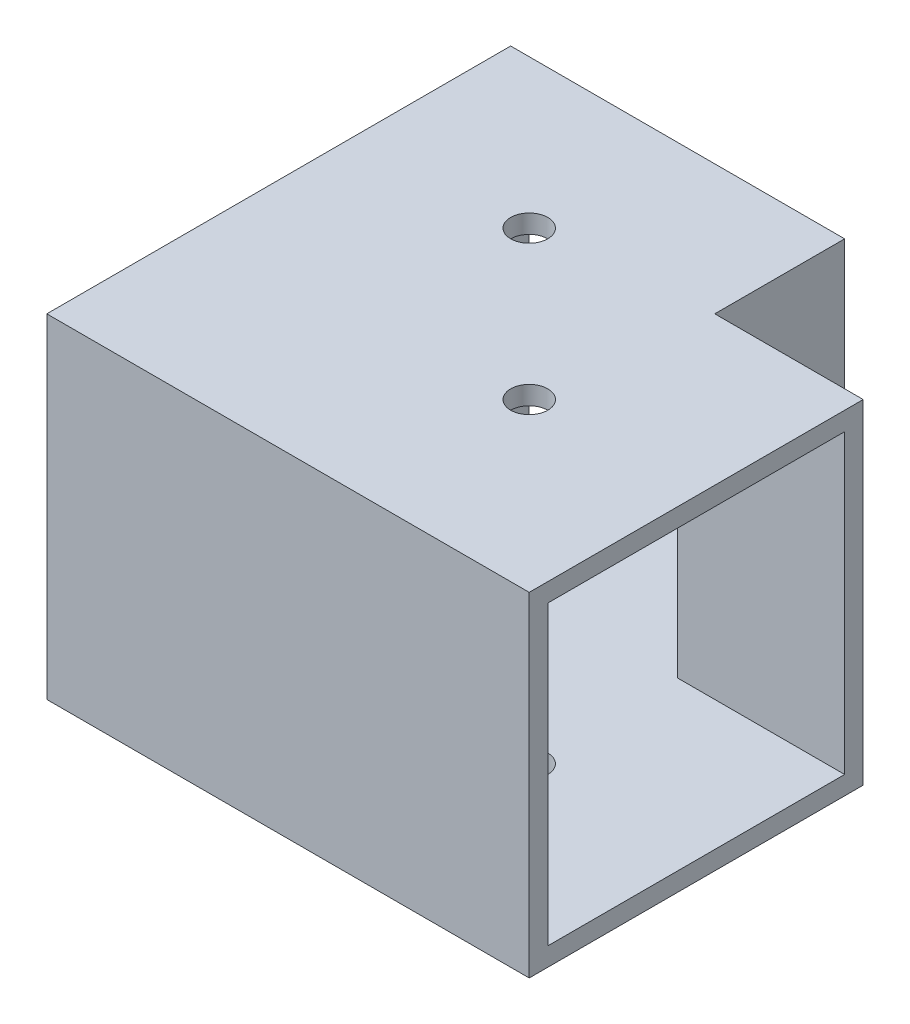
SolidWorks part; units mm, degrees
ref_plane "Front Plane" through (0, 0, 0) normal (0, 0, 1) x (1, 0, 0)
ref_plane "Top Plane" through (0, 0, 0) normal (0, 1, 0) x (1, 0, 0)
ref_plane "Right Plane" through (0, 0, 0) normal (1, 0, 0) x (0, 0, -1)
sketch "Sketch1" plane through (0, 0, 0) normal (0, 0, 1) x (1, 0, 0)
  line L1 (-50.8, -50.8) -> (50.8, -50.8)
  line L2 (-50.8, -50.8) -> (-50.8, 50.8)
  line L3 (-50.8, 50.8) -> (50.8, 50.8)
  line L4 (50.8, -50.8) -> (50.8, 50.8)
  line L5 (-50.8, -50.8) -> (50.8, 50.8) construction
  line L6 (-50.8, 50.8) -> (50.8, -50.8) construction
  point P0 (0, 0)
  dimension "D1" = 101.6
  dimension "D2" = 101.6
extrude "Extrude-Thin1" add sketch "Sketch1" along normal blind 50.8 thin
sketch "Sketch3" plane through (57.15, 0, 0) normal (1, 0, 0) x (0, 0, -1)
  line L0 (-50.8, 57.15) -> (0, 57.15) construction
  line L1 (-50.8, -50.8) -> (-152.4, -50.8)
  line L2 (-50.8, -50.8) -> (-50.8, 50.8)
  line L3 (-50.8, 50.8) -> (-152.4, 50.8)
  line L4 (-152.4, -50.8) -> (-152.4, 50.8)
  line L5 (-50.8, -57.15) -> (0, -57.15) construction
  line L6 (-50.8, -57.15) -> (-50.8, 57.15) construction
  dimension "D1" = 6.35
  dimension "D2" = 6.35
  dimension "D3" = 0
  dimension "D4" = 101.6
extrude "Extrude-Thin2" add sketch "Sketch3" along normal blind 50.8 thin thin type one direction wall 6.35
sketch "Sketch4" plane through (57.15, 0, 0) normal (-1, 0, 0) x (0, 0, 1)
  line L8 (50.8, -50.8) -> (50.8, -57.15)
  line L9 (50.8, -57.15) -> (158.75, -57.15)
  line L10 (158.75, -57.15) -> (158.75, 57.15)
  line L11 (158.75, 57.15) -> (50.8, 57.15)
  line L12 (50.8, 57.15) -> (50.8, 50.8)
  line L13 (50.8, 50.8) -> (152.4, 50.8)
  line L14 (152.4, 50.8) -> (152.4, -50.8)
  line L15 (152.4, -50.8) -> (50.8, -50.8)
  line L16 (50.8, -50.8) -> (50.8, -57.15)
  line L17 (50.8, -57.15) -> (158.75, -57.15)
  line L18 (158.75, -57.15) -> (158.75, 57.15)
  line L19 (158.75, 57.15) -> (50.8, 57.15)
  line L20 (50.8, 57.15) -> (50.8, 50.8)
  line L21 (50.8, 50.8) -> (152.4, 50.8)
  line L22 (152.4, 50.8) -> (152.4, -50.8)
  line L23 (152.4, -50.8) -> (50.8, -50.8)
  dimension "D1" = 0
extrude "Boss-Extrude1" add sketch "Sketch4" along normal up to surface (114.3 mm away) up to face at (-57.15, 0, 25.4)
sketch "Sketch5" plane through (0, 0, 50.8) normal (0, 0, 1) x (1, 0, 0)
  line L4 (-50.8, -50.8) -> (-50.8, 50.8)
  line L5 (-50.8, 50.8) -> (-57.15, 50.8)
  line L6 (-57.15, 50.8) -> (-57.15, -50.8)
  line L7 (-57.15, -50.8) -> (-50.8, -50.8)
  line L8 (-50.8, -50.8) -> (-50.8, 50.8)
  line L9 (-50.8, 50.8) -> (-57.15, 50.8)
  line L10 (-57.15, 50.8) -> (-57.15, -50.8)
  line L11 (-57.15, -50.8) -> (-50.8, -50.8)
  dimension "D1" = 0
extrude "Boss-Extrude2" add sketch "Sketch5" along normal up to surface (101.6 mm away)
sketch "Sketch6" plane through (0, 57.15, 0) normal (0, 1, 0) x (1, 0, 0)
  line L0 (0, 0) -> (0, -50.8) construction
  circle A0 centre (0, -50.8) radius 6.35
  dimension "D1" = 12.7
  dimension "D2" = 50.8
ref_plane "Plane1" through (50.8, 0, 50.8) normal (0.7071, 0, 0.7071) x (0.7071, 0, -0.7071)
extrude "Cut-Extrude1" cut sketch "Sketch6" against normal through all
mirror "Mirror1" about plane through (50.8, 0, 50.8) normal (0.7071, 0, 0.7071) of "Cut-Extrude1"
